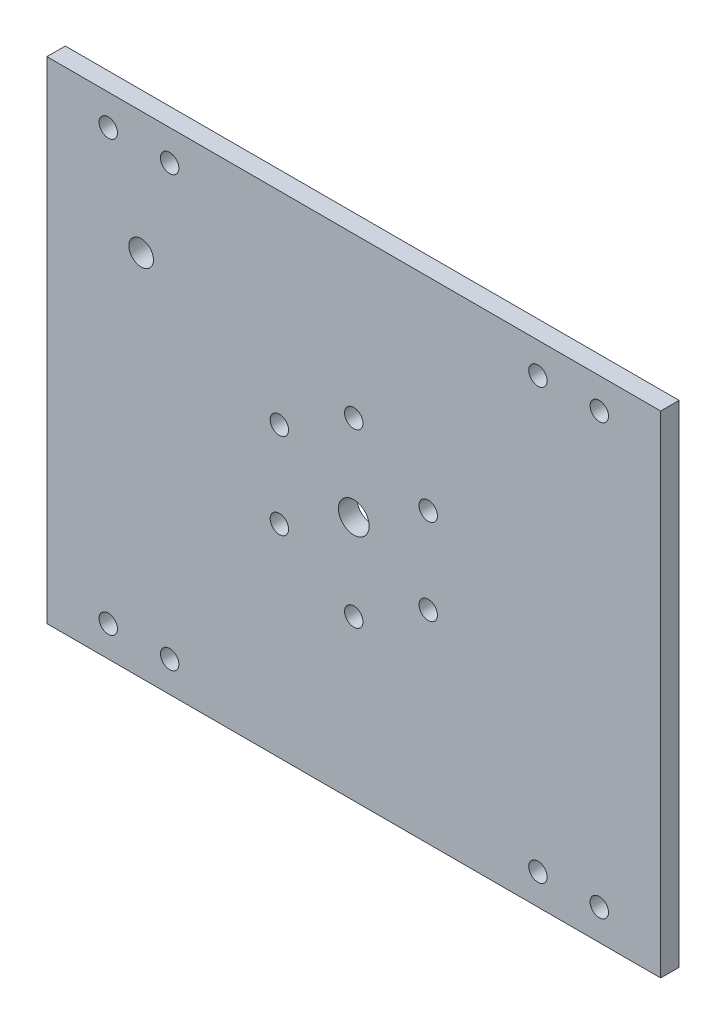
SolidWorks part; units mm, degrees
material "7050-T73510"
ref_plane "前视基准面" through (0, 0, 0) normal (0, 0, 1) x (1, 0, 0)
ref_plane "上视基准面" through (0, 0, 0) normal (0, 1, 0) x (1, 0, 0)
ref_plane "右视基准面" through (0, 0, 0) normal (1, 0, 0) x (0, 0, -1)
sketch "草图1" plane through (0, 0, 0) normal (0, 0, 1) x (1, 0, 0)
  line L1 (-50, 40) -> (50, 40)
  line L2 (-50, 40) -> (-50, -40)
  line L3 (-50, -40) -> (50, -40)
  line L4 (50, 40) -> (50, -40)
  line L5 (0, -40) -> (0, 40) construction
  line L6 (-50, 0) -> (50, 0) construction
  circle A0 centre (0, 0) radius 14 construction
  circle A1 centre (0, 14) radius 1.5
  circle A2 centre (12.1244, 7) radius 1.5
  circle A3 centre (12.1244, -7) radius 1.5
  circle A4 centre (0, -14) radius 1.5
  circle A5 centre (-12.1244, -7) radius 1.5
  circle A6 centre (-12.1244, 7) radius 1.5
  circle A7 centre (0, 0) radius 2.5
  point P0 (0, 0)
  point P20 (0, 0)
  dimension "D3" = 28
  dimension "D4" = 3
  dimension "D6" = 5
  dimension "D1" = 80
  dimension "D2" = 100
  dimension "D5" = 6
extrude "凸台-拉伸1" add sketch "草图1" along normal blind 3
sketch "草图2" plane through (0, 0, 0) normal (0, 0, -1) x (-1, 0, 0)
  line L0 (-50, -40) -> (-50, 40) construction
  line L1 (0, 52.0185) -> (0, -49.9837) construction
  line L2 (-85.3988, 0) -> (73.0427, 0) construction
  circle A0 centre (0, 0) radius 35 construction
  circle A1 centre (-40, 35) radius 1.5
  circle A2 centre (-30, 35) radius 1.5
  circle A3 centre (30, 35) radius 1.5
  circle A4 centre (40, 35) radius 1.5
  circle A5 centre (40, -35) radius 1.5
  circle A6 centre (30, -35) radius 1.5
  circle A7 centre (-30, -35) radius 1.5
  circle A8 centre (-40, -35) radius 1.5
  dimension "D1" = 70
  dimension "D3" = 10
  dimension "D4" = 3
  dimension "D5" = 10
  dimension "D2" = 35
extrude "切除-拉伸1" cut sketch "草图2" against normal blind 10
sketch "草图3" plane through (0, 0, 0) normal (0, 0, -1) x (-1, 0, 0)
  line L0 (-61.2673, 0) -> (54.8294, 0) construction
  line L1 (0, 0) -> (34.641, 20) construction
  circle A0 centre (0, 0) radius 40 construction
  circle A1 centre (34.641, 20) radius 2
  dimension "D1" = 80
  dimension "D3" = 4
  dimension "D2" = 30
extrude "切除-拉伸2" cut sketch "草图3" against normal through all
